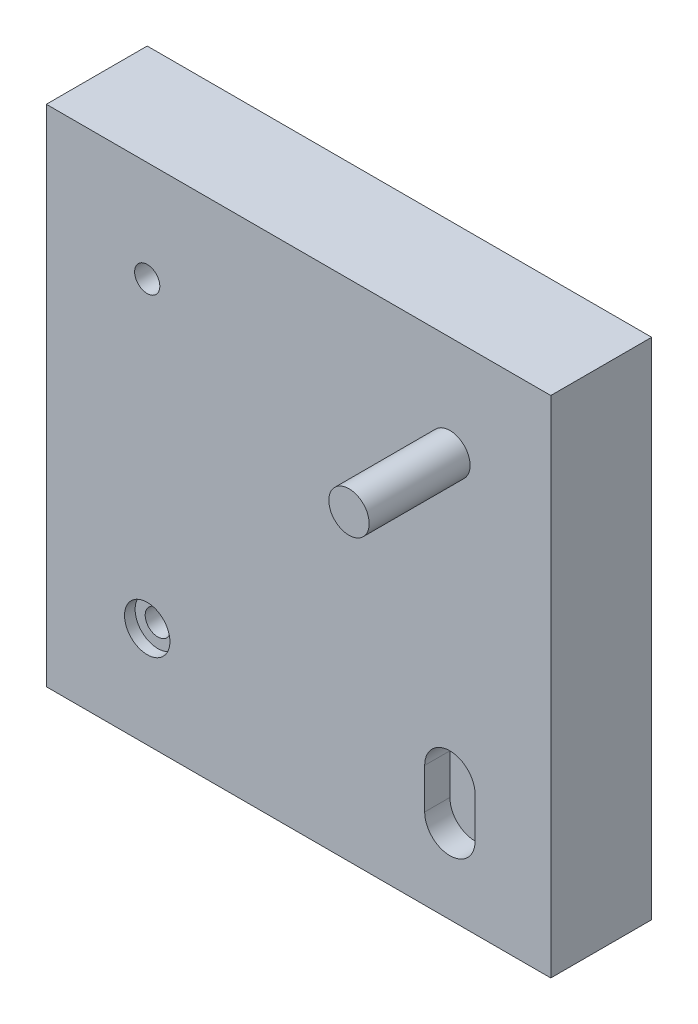
SolidWorks part; units mm, degrees
material "1.4301 (X5CrNi18-10)"
ref_plane "Ebene vorne" through (0, 0, 0) normal (0, 0, 1) x (1, 0, 0)
ref_plane "Ebene oben" through (0, 0, 0) normal (0, 1, 0) x (1, 0, 0)
ref_plane "Ebene rechts" through (0, 0, 0) normal (1, 0, 0) x (0, 0, -1)
sketch "Skizze1" plane through (0, 0, 0) normal (0, 0, 1) x (1, 0, 0)
  line L1 (-50, -50) -> (50, -50)
  line L2 (-50, -50) -> (-50, 50)
  line L3 (-50, 50) -> (50, 50)
  line L4 (50, -50) -> (50, 50)
  line L5 (0, 50) -> (0, -50) construction
  line L6 (-50, 0) -> (50, 0) construction
  point P0 (0, 0)
  dimension "D1" = 100
extrude "Aufsatz-Linear austragen1" add sketch "Skizze1" along normal blind 20
sketch "Skizze4" plane through (0, 0, 20) normal (0, 0, 1) x (1, 0, 0)
  point P0 (-30, 30)
  dimension "D1" = 30
  dimension "D2" = 30
hole_wizard "Ø5.0mm Stiftloch1" positions "Skizze4" profile "Skizze3" hole size "Ø5.0" standard "ISO"
sketch "Skizze3" plane through (-30, 30, 20) normal (1, 0, 0) x (0, -1, 0)
  line L0 (0, 0) -> (0, 10.0022)
  line L1 (0, 10.0022) -> (2.5, 8.5)
  line L2 (2.5, 8.5) -> (2.5, 0)
  line L5 (2.5, 0) -> (0, 0)
  line L10 (0, 10.0022) -> (-2.5, 8.5) construction
  line L11 (0, -6.35) -> (0, 107.95) construction
  dimension "Bohrerdurchmesser" = 5
  dimension "Bohrungstiefe" = 8.5
  dimension "Spitzenwinkel" = 118
sketch "Skizze5" plane through (0, 0, 20) normal (0, 0, 1) x (1, 0, 0)
  circle A0 centre (30, 30) radius 4
  dimension "D1" = 30
  dimension "D3" = 8
  dimension "D2" = 30
extrude "Aufsatz-Linear austragen2" add sketch "Skizze5" along normal blind 20
sketch "Skizze8" plane through (0, 0, 20) normal (0, 0, 1) x (1, 0, 0)
  point P0 (-30, -30)
  point P8 (-2.4438, -1.7456)
  dimension "D1" = 30
  dimension "D2" = 30
hole_wizard "Bohrung1" positions "Skizze8" profile "Skizze7" legacy end condition through all
sketch "Skizze7" plane through (-30, -30, 20) normal (1, 0, 0) x (0, -1, 0)
  line L0 (0, 0) -> (0, 21.5022)
  line L1 (0, 21.5022) -> (2.5, 20)
  line L2 (2.5, 20) -> (2.5, 2.1)
  line L3 (2.5, 2.1) -> (4.5, 2.1)
  line L4 (4.5, 0) -> (0, 0)
  line L5 (0, -11.3109) -> (0, 121.1557) construction
  line L6 (0, 21.5022) -> (-2.5, 20) construction
  line L7 (4.5, 2.1) -> (4.5, 0)
  dimension "Durchmesser" = 5
  dimension "Tiefe" = 20
  dimension "Senkdurchmesser3" = 9
  dimension "Senktiefe1" = 2.1
  dimension "Spitzenwinkel" = 118
sketch "Skizze9" plane through (0, 0, 20) normal (0, 0, 1) x (1, 0, 0)
  line L0 (30, -34) -> (30, -26) construction
  line L1 (25, -34) -> (25, -26)
  line L2 (35, -34) -> (35, -26)
  arc A0 (25, -34) -> (35, -34) centre (30, -34) ccw
  arc A1 (35, -26) -> (25, -26) centre (30, -26) ccw
  point P2 (30, -30)
  dimension "D1" = 30
  dimension "D2" = 30
  dimension "D3" = 10
  dimension "D4" = 8
extrude "Schnitt-Linear austragen1" cut sketch "Skizze9" against normal blind 5
